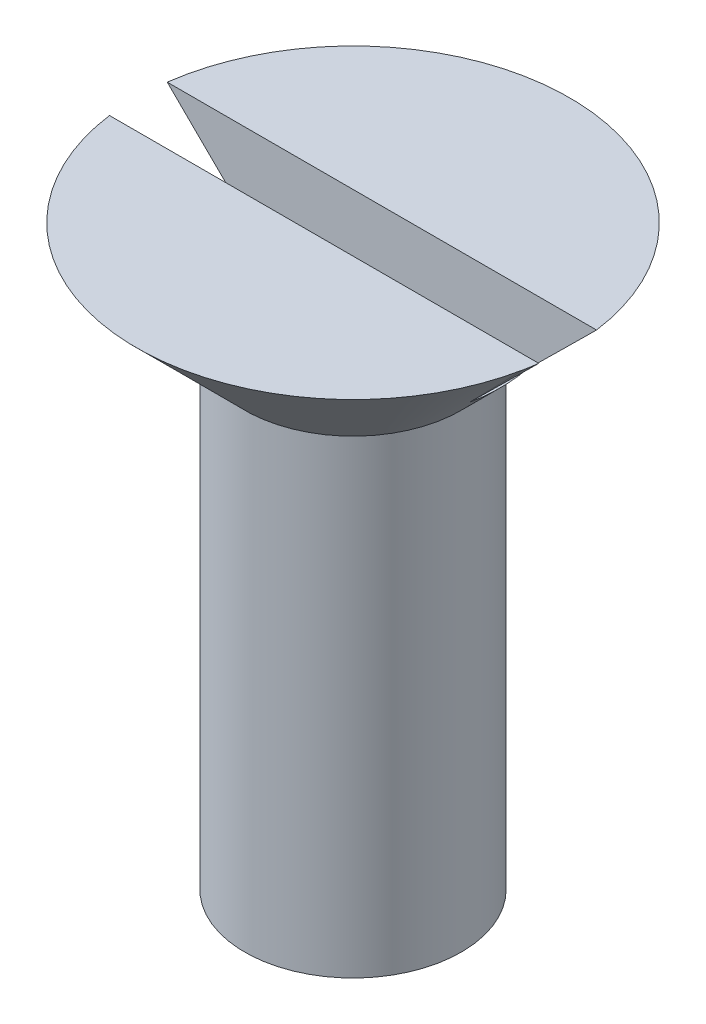
SolidWorks part; units mm, degrees
material "201 Annealed Stainless Steel (SS)"
ref_plane "Front Plane" through (0, 0, 0) normal (0, 0, 1) x (1, 0, 0)
ref_plane "Top Plane" through (0, 0, 0) normal (0, 1, 0) x (1, 0, 0)
ref_plane "Right Plane" through (0, 0, 0) normal (1, 0, 0) x (0, 0, -1)
sketch "Sketch1" plane through (0, 0, 0) normal (0, 0, 1) x (1, 0, 0)
  line L0 (0, 0) -> (0, 33.3711) construction
  line L1 (0, 0) -> (3, 0)
  line L2 (3, 0) -> (3, 13)
  line L3 (3, 13) -> (6, 16)
  line L4 (6, 16) -> (0, 16)
  line L5 (0, 0) -> (0, 16)
  dimension "D1" = 13
  dimension "D2" = 6
  dimension "D3" = 3
  dimension "D4" = 45
revolve "Revolve1" add sketch "Sketch1" angle 360 about L0
sketch "Sketch2" plane through (0, 16, 0) normal (0, 1, 0) x (1, 0, 0)
  line L1 (-8.3128, -0.8) -> (8.3128, -0.8)
  line L2 (-8.3128, -0.8) -> (-8.3128, 0.8)
  line L3 (-8.3128, 0.8) -> (8.3128, 0.8)
  line L4 (8.3128, -0.8) -> (8.3128, 0.8)
  line L5 (-8.3128, -0.8) -> (8.3128, 0.8) construction
  line L6 (-8.3128, 0.8) -> (8.3128, -0.8) construction
  point P0 (0, 0)
  dimension "D1" = 1.6
extrude "Cut-Extrude1" cut sketch "Sketch2" against normal blind 1.9
